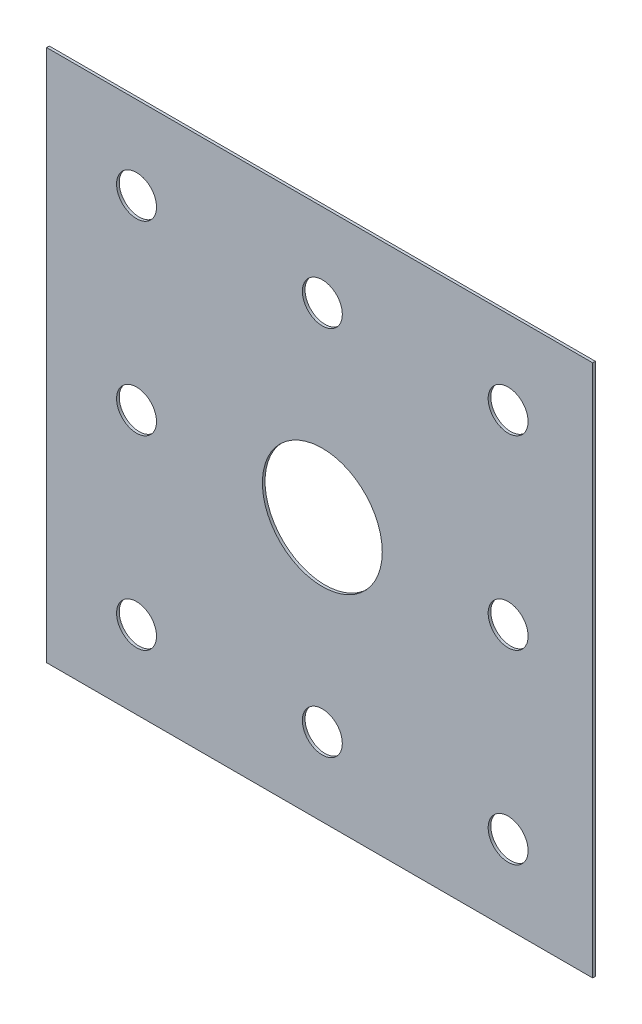
SolidWorks part; units mm, degrees
ref_plane "정면" through (0, 0, 0) normal (0, 0, 1) x (1, 0, 0)
ref_plane "윗면" through (0, 0, 0) normal (0, 1, 0) x (1, 0, 0)
ref_plane "우측면" through (0, 0, 0) normal (1, 0, 0) x (0, 0, -1)
sketch "스케치1" plane through (0, 0, 0) normal (0, 0, 1) x (1, 0, 0)
  line L4 (0, 40) -> (41, 40)
  line L5 (0, 40) -> (0, 0)
  line L6 (0, 0) -> (41, 0)
  line L7 (41, 40) -> (41, 0)
  dimension "D1" = 41
  dimension "D2" = 40
extrude "보스-돌출1" add sketch "스케치1" along normal blind 0.2
sketch "스케치5" plane through (0, 0, 0.2) normal (0, 0, 1) x (1, 0, 0)
  line L0 (41, 40) -> (0, 40) construction
  line L1 (41, 0) -> (41, 40) construction
  circle A0 centre (20.7, 19.8) radius 4.5
  dimension "D1" = 9
  dimension "D2" = 20.2
  dimension "D3" = 20.3
extrude "컷-돌출3" cut sketch "스케치5" against normal blind 0.2
sketch "스케치6" plane through (0, 0, 0.2) normal (0, 0, 1) x (1, 0, 0)
  line L1 (41, 0) -> (41, 40) construction
  line L3 (0, 40) -> (0, 0) construction
  line L4 (41, 40) -> (0, 40) construction
  circle A9 centre (20.7, 19.8) radius 4.5 construction
  circle A10 centre (20.7, 19.8) radius 4.5
  circle A11 centre (34.65, 19.8) radius 1.5
  circle A12 centre (20.7, 19.8) radius 4.5
  circle A13 centre (34.65, 5.85) radius 1.5
  circle A14 centre (20.7, 5.85) radius 1.5
  circle A15 centre (6.75, 19.8) radius 1.5
  circle A16 centre (20.7, 33.75) radius 1.5
  circle A17 centre (6.75, 5.85) radius 1.5
  circle A18 centre (6.75, 33.75) radius 1.5
  circle A19 centre (34.65, 33.75) radius 1.5
  point P0 (34.65, 5.85)
  point P9 (20.7, 19.8)
  point P13 (20.7, 19.8)
  point P17 (20.7, 19.8)
  point P28 (20.7, 19.8)
  dimension "D1" = 4
  dimension "D2" = 3
  dimension "D8" = 3
  dimension "D4" = 13.95
  dimension "D5" = 13.95
  dimension "D6" = 13.95
  dimension "D7" = 6.35
  dimension "D9" = 6.75
  dimension "D10" = 6.25
  dimension "D3" = 4
extrude "컷-돌출4" cut sketch "스케치6" against normal blind 0.2 contours A16 | A19 | A11 | A14 | A13 | A17 | A18 | A15
